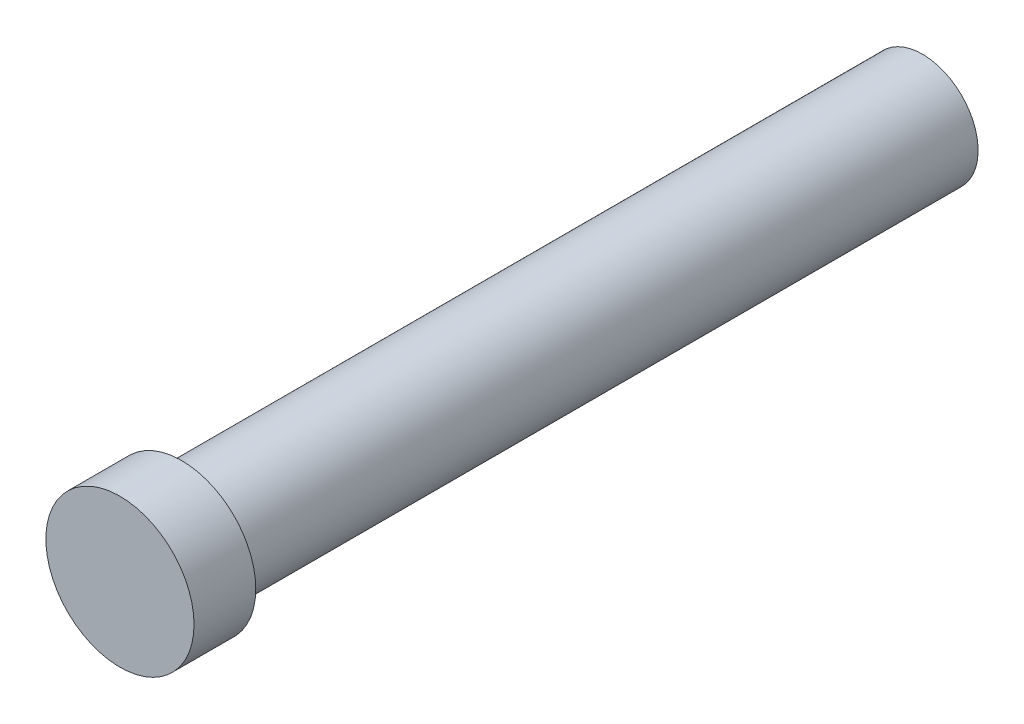
SolidWorks part; units mm, degrees
ref_plane "前视基准面" through (0, 0, 0) normal (0, 0, 1) x (1, 0, 0)
ref_plane "上视基准面" through (0, 0, 0) normal (0, 1, 0) x (1, 0, 0)
ref_plane "右视基准面" through (0, 0, 0) normal (1, 0, 0) x (0, 0, -1)
other "Configuration Table"
sketch "草图1" plane through (0, 0, 0) normal (0, 0, 1) x (1, 0, 0)
  circle A0 centre (0, 0) radius 6
  dimension "D1" = 12
extrude "凸台-拉伸1" add sketch "草图1" along normal blind 5
sketch "草图2" plane through (0, 0, 0) normal (0, 0, -1) x (-1, 0, 0)
  circle A0 centre (0, 0) radius 4.5
  dimension "D1" = 9
extrude "凸台-拉伸2" add sketch "草图2" along normal blind 60
